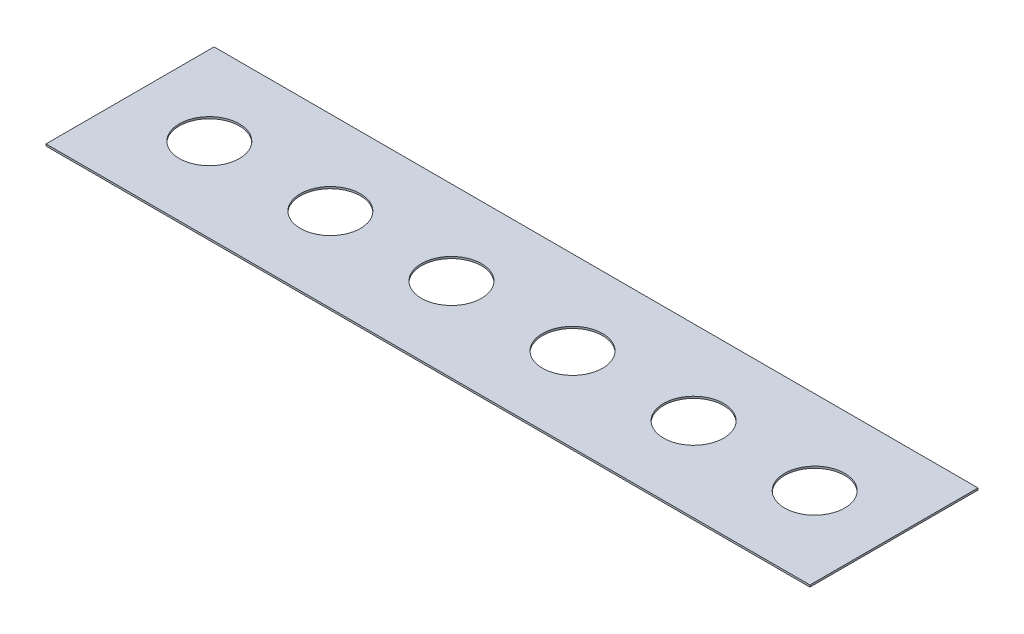
SolidWorks part; units mm, degrees
ref_plane "Front" through (0, 0, 0) normal (0, 0, 1) x (1, 0, 0)
ref_plane "Top" through (0, 0, 0) normal (0, 1, 0) x (1, 0, 0)
ref_plane "Right" through (0, 0, 0) normal (1, 0, 0) x (0, 0, -1)
sketch "Sketch1" plane through (0, 0, 0) normal (0, 1, 0) x (1, 0, 0)
  line L0 (-317.5, 0) -> (317.5, 0) construction
  line L1 (-317.5, -69.85) -> (317.5, -69.85)
  line L2 (-317.5, -69.85) -> (-317.5, 69.85)
  line L3 (-317.5, 69.85) -> (317.5, 69.85)
  line L4 (317.5, -69.85) -> (317.5, 69.85)
  line L5 (-317.5, -69.85) -> (317.5, 69.85) construction
  line L6 (-317.5, 69.85) -> (317.5, -69.85) construction
  circle A0 centre (-251.587, 0) radius 24.9936
  circle A3 centre (-150.9522, 0) radius 24.9936
  circle A4 centre (-50.3174, 0) radius 24.9936
  circle A5 centre (50.3174, 0) radius 24.9936
  circle A6 centre (150.9522, 0) radius 24.9936
  circle A7 centre (251.587, 0) radius 24.9936
  point P0 (0, 0)
  point P10 (0, 0)
  dimension "D6" = 49.9872
  dimension "D1" = 635
  dimension "D2" = 139.7
  dimension "D3" = 65.913
  dimension "D5" = 100.6348
  dimension "D4" = 6
extrude "Boss-Extrude1" add sketch "Sketch1" along normal blind 1.5748
equation "\"gap\"=3.962"
equation "\"buffer\"= ( \"length\" - ( \"gap\" * 5 ) ) / 2"
equation "\"D3@Sketch1\"=\"buffer\""
equation "\"D5@Sketch1\"=\"gap\""
equation "\"length\"=25"
equation "\"D1@Sketch1\"=\"length\""
